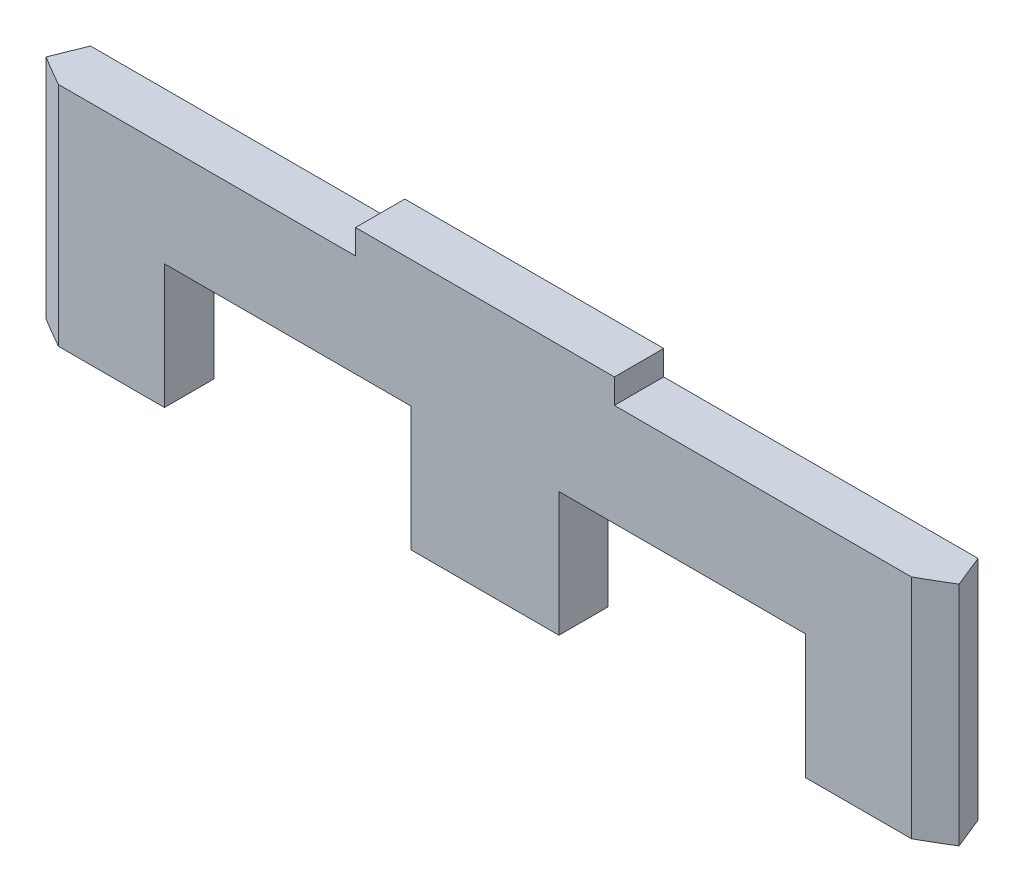
SolidWorks part; units mm, degrees
ref_plane "Front Plane" through (0, 0, 0) normal (0, 0, 1) x (1, 0, 0)
ref_plane "Top Plane" through (0, 0, 0) normal (0, 1, 0) x (1, 0, 0)
ref_plane "Right Plane" through (0, 0, 0) normal (1, 0, 0) x (0, 0, -1)
sketch "Sketch1" plane through (0, 0, 0) normal (0, 0, 1) x (1, 0, 0)
  line L0 (3, -2.075) -> (13, -2.075)
  line L1 (-18, 2.075) -> (-5.25, 2.075)
  line L2 (-18, 2.075) -> (-18, -2.075)
  line L3 (-13, -2.075) -> (-3, -2.075)
  line L4 (18, 2.075) -> (18, -2.075)
  line L5 (-18, 2.075) -> (18, -2.075) construction
  line L6 (-18, -2.075) -> (18, 2.075) construction
  line L8 (-18, -2.075) -> (-18, -7.125)
  line L9 (-18, -7.125) -> (-13, -7.125)
  line L10 (-13, -2.075) -> (-13, -7.125)
  line L11 (-18, -2.075) -> (-13, -7.125) construction
  line L12 (-18, -7.125) -> (-13, -2.075) construction
  line L14 (18, -2.075) -> (18, -7.125)
  line L15 (18, -7.125) -> (13, -7.125)
  line L16 (13, -2.075) -> (13, -7.125)
  line L17 (18, -2.075) -> (13, -7.125) construction
  line L18 (18, -7.125) -> (13, -2.075) construction
  line L20 (3, -2.075) -> (3, -7.125)
  line L21 (3, -7.125) -> (-3, -7.125)
  line L22 (-3, -2.075) -> (-3, -7.125)
  line L23 (3, -2.075) -> (-3, -7.125) construction
  line L24 (3, -7.125) -> (-3, -2.075) construction
  line L25 (5.25, 2.075) -> (18, 2.075)
  line L27 (-5.25, 2.075) -> (-5.25, 3.075)
  line L28 (-5.25, 3.075) -> (5.25, 3.075)
  line L29 (5.25, 2.075) -> (5.25, 3.075)
  line L30 (-5.25, 2.075) -> (5.25, 3.075) construction
  line L31 (-5.25, 3.075) -> (5.25, 2.075) construction
  point P4 (0, 0)
  point P8 (-15.5, -4.6)
  point P12 (15.5, -4.6)
  point P17 (0, -4.6)
  point P25 (0, 2.575)
  dimension "D1" = 5.05
  dimension "D2" = 4.15
  dimension "D3" = 36
  dimension "D4" = 26
  dimension "D5" = 6
  dimension "D6" = 1
  dimension "D7" = 10.5
extrude "Boss-Extrude1" add sketch "Sketch1" along normal blind 2
sketch "Sketch2" plane through (0, 2.075, 0) normal (0, 1, 0) x (1, 0, 0)
  line L0 (-18, 0) -> (-18.8068, -2)
  line L1 (-18.8068, -2) -> (-18, -2)
  line L2 (-18, -2) -> (-18, 0)
  line L3 (18, 0) -> (18, -2)
  line L4 (18, -2) -> (18.8068, -2)
  line L5 (18.8068, -2) -> (18, 0)
  line L6 (16, 5.1135) -> (18.5694, -1.256) construction
extrude "Boss-Extrude2" add sketch "Sketch2" against normal up to surface (9.2 mm away) up to face at (-15.5, -7.125, 1)
sketch "Sketch3" plane through (0, 2.075, 0) normal (0, 1, 0) x (1, 0, 0)
  line L0 (-18, 0) -> (-18.8068, -2) construction
  line L1 (-5.25, -2) -> (-18.8068, -2) construction
  line L2 (18.8068, -2) -> (5.25, -2) construction
  line L3 (18.8068, -2) -> (18, 0) construction
  line L4 (-18.5191, -1.2868) -> (-18.8068, -2)
  line L5 (-17.2988, -2) -> (-18.8068, -2)
  line L6 (18.8068, -2) -> (17.2988, -2)
  line L7 (18.8068, -2) -> (18.5191, -1.2868)
  arc A0 (-18.5191, -1.2868) -> (-17.2988, -2) centre (0, 29) ccw
  arc A1 (18.5694, -1.256) -> (-18.5694, -1.256) centre (0, 29) ccw construction
  arc A2 (17.2988, -2) -> (18.5191, -1.2868) centre (0, 29) ccw
extrude "Cut-Extrude1" cut sketch "Sketch3" against normal up to next
